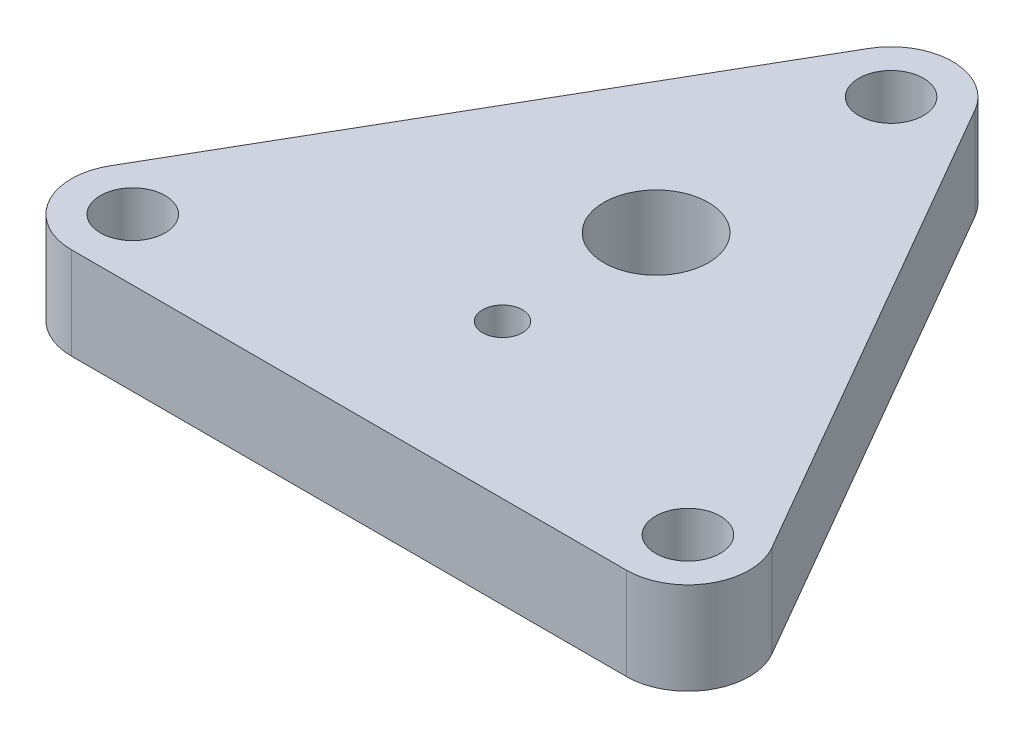
SolidWorks part; units mm, degrees
ref_plane "Front Plane" through (0, 0, 0) normal (0, 0, 1) x (1, 0, 0)
ref_plane "Top Plane" through (0, 0, 0) normal (0, 1, 0) x (1, 0, 0)
ref_plane "Right Plane" through (0, 0, 0) normal (1, 0, 0) x (0, 0, -1)
sketch "Sketch1" plane through (0, 0, 0) normal (0, 1, 0) x (1, 0, 0)
  line L0 (0, 0) -> (9.0359, 0)
  line L1 (10.7679, 3) -> (1.7321, 18.6506)
  line L2 (-1.7321, 18.6506) -> (-10.7679, 3)
  line L3 (-9.0359, 0) -> (0, 0)
  arc A0 (9.0359, 0) -> (10.7679, 3) centre (9.0359, 2) ccw
  arc A1 (-10.7679, 3) -> (-9.0359, 0) centre (-9.0359, 2) ccw
  arc A2 (1.7321, 18.6506) -> (-1.7321, 18.6506) centre (0, 17.6506) ccw
  circle A3 centre (0, 17.6506) radius 1.054
  circle A4 centre (-9.0359, 2) radius 1.054
  circle A5 centre (9.0359, 2) radius 1.054
  point P7 (12.5, 0)
  point P10 (-12.5, 0)
  point P13 (0, 21.6506)
  dimension "D5" = 2
  dimension "D1" = 60
  dimension "D2" = 60
  dimension "D3" = 25
  dimension "D4" = 12.5
extrude "Boss-Extrude1" add sketch "Sketch1" along normal blind 3
sketch "Sketch2" plane through (0, 3, 0) normal (0, 1, 0) x (1, 0, 0)
  line L0 (-9.0359, 0) -> (9.0359, 0) construction
  circle A0 centre (0, 10) radius 1.702
  circle A1 centre (0, 5) radius 0.65
  point P2 (0, 0)
  point P7 (0, 0)
  dimension "D1" = 10
  dimension "D2" = 5
extrude "Cut-Extrude1" cut sketch "Sketch2" against normal through all
